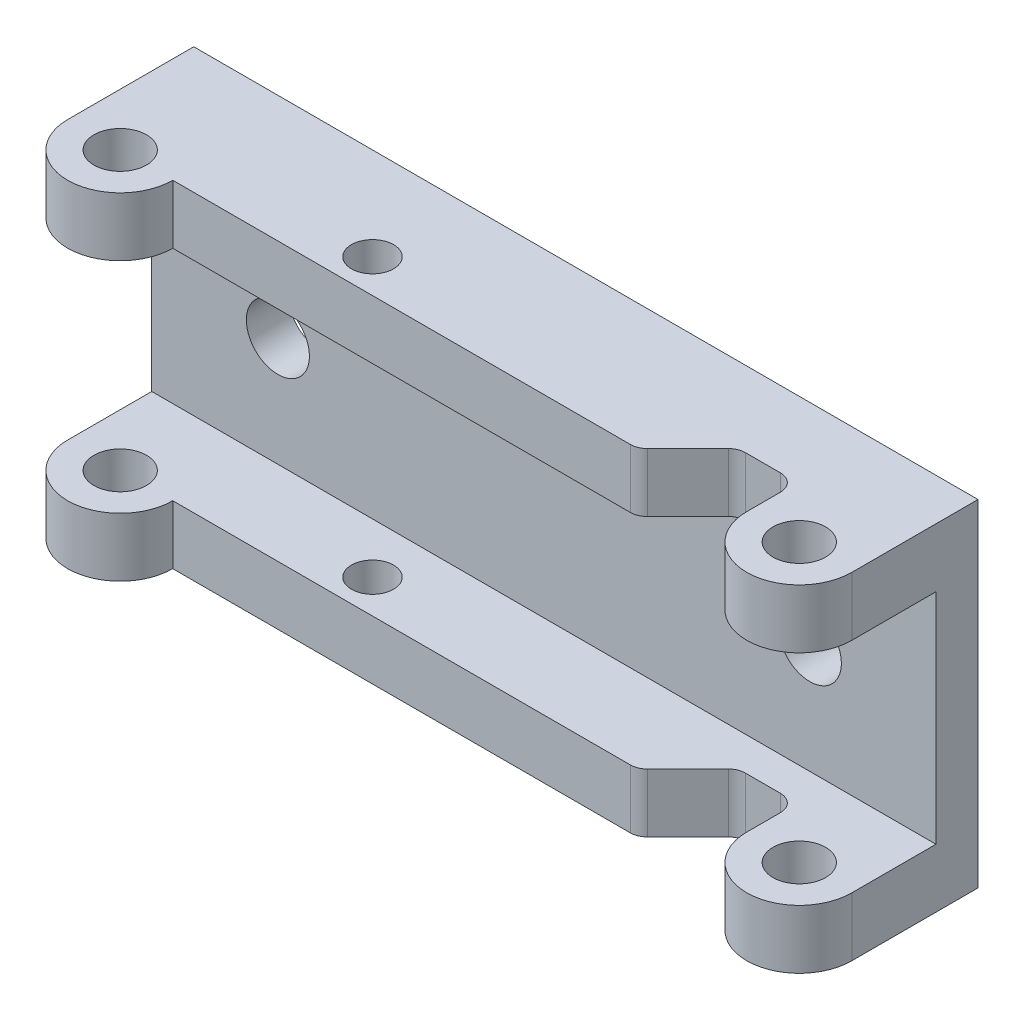
SolidWorks part; units mm, degrees
material "7075-T6 (SN)"
ref_plane "X-Y Datum" through (0, 0, 0) normal (0, 0, 1) x (1, 0, 0)
ref_plane "X-Z Datum" through (0, 0, 0) normal (0, 1, 0) x (1, 0, 0)
ref_plane "Y-Z Datum" through (0, 0, 0) normal (1, 0, 0) x (0, 0, -1)
sketch "Sketch2" plane through (0, 0, 0) normal (1, 0, 0) x (0, 0, -1)
  line L0 (0, -25.4) -> (0, 25.4)
  line L1 (0, 25.4) -> (-63.5, 25.4)
  line L2 (-63.5, 25.4) -> (-63.5, 16.51)
  line L3 (-63.5, 16.51) -> (-6.35, 16.51)
  line L4 (-6.35, 16.51) -> (-6.35, -16.51)
  line L6 (-6.35, 0) -> (0, 0) construction
  line L7 (0, -25.4) -> (-63.5, -25.4)
  line L8 (-63.5, -25.4) -> (-63.5, -16.51)
  line L9 (-63.5, -16.51) -> (-6.35, -16.51)
  dimension "D1" = 16.51
  dimension "D2" = 6.35
  dimension "D3" = 57.15
  dimension "D4" = 8.89
extrude "Boss-Extrude1" add sketch "Sketch2" along normal blind 118.4275
sketch "Sketch3" plane through (0, 0, 0) normal (0, 1, 0) x (1, 0, 0)
  line L0 (0, 0) -> (0, -63.5) construction
  line L1 (118.4275, -6.35) -> (0, -6.35) construction
  line L5 (0, -63.5) -> (0, -19.05)
  line L7 (102.5525, -19.05) -> (102.5525, -13.97)
  line L9 (118.4275, -63.5) -> (0, -63.5)
  line L10 (118.4275, -63.5) -> (118.4275, -19.05)
  line L12 (110.49, -19.05) -> (118.4275, -19.05) construction
  line L14 (100.0125, -11.43) -> (94.7146, -11.43)
  line L16 (15.875, -19.05) -> (84.9904, -19.05)
  line L17 (86.7864, -18.3061) -> (92.9186, -12.1739)
  circle A0 centre (7.9375, -19.05) radius 3.9688
  circle A1 centre (110.49, -19.05) radius 3.9688
  arc A3 (100.0125, -11.43) -> (102.5525, -13.97) centre (100.0125, -13.97) cw
  arc A5 (0, -19.05) -> (15.875, -19.05) centre (7.9375, -19.05) ccw
  arc A7 (102.5525, -19.05) -> (118.4275, -19.05) centre (110.49, -19.05) ccw
  arc A10 (84.9904, -19.05) -> (86.7864, -18.3061) centre (84.9904, -16.51) ccw
  arc A11 (92.9186, -12.1739) -> (94.7146, -11.43) centre (94.7146, -13.97) cw
  circle A12 centre (40.9575, -13.97) radius 3.175
  point P14 (41.5789, -14.605)
  point P23 (102.5525, -11.43)
  point P30 (93.6625, -11.43)
  point P33 (0, 0)
  point P34 (52.6061, -12.1739)
  dimension "D1" = 7.9375
  dimension "D2" = 7.9375
  dimension "D6" = 7.62
  dimension "D10" = 7.9375
  dimension "D11" = 7.9375
  dimension "D7" = 33.02
  dimension "D14" = 2.54
  dimension "D15" = 6.35
  dimension "D3" = 5.08
  dimension "D4" = 7.9375
  dimension "D5" = 12.7
  dimension "D8" = 8.89
  dimension "D13" = 135
extrude "Cut-Extrude1" cut sketch "Sketch3" against normal up to surface and the other way up to surface up to face at (59.2137, -25.4, 31.75) other way up to face at (59.2137, 25.4, 31.75)
sketch "Sketch4" plane through (0, 0, 0) normal (0, 0, 1) x (1, 0, 0)
  line L0 (0, -25.4) -> (0, 25.4) construction
  line L1 (118.4275, 16.51) -> (118.4275, -16.51) construction
  circle A0 centre (19.05, 0) radius 4.7625
  circle A1 centre (99.3775, 0) radius 4.7625
  dimension "D1" = 9.525
  dimension "D2" = 19.05
  dimension "D3" = 19.05
extrude "Cut-Extrude2" cut sketch "Sketch4" along normal up to surface (6.35 mm away) up to face at (59.2137, 0, 6.35)
